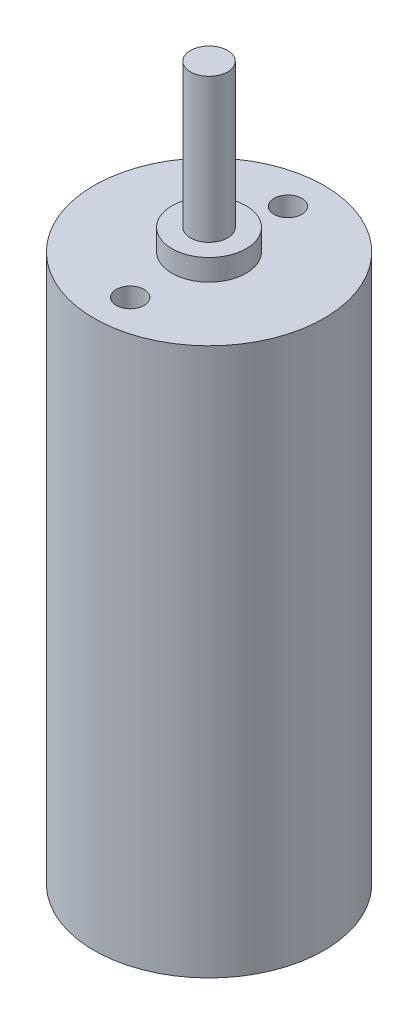
SolidWorks part; units mm, degrees
ref_plane "Front Plane" through (0, 0, 0) normal (0, 0, 1) x (1, 0, 0)
ref_plane "Top Plane" through (0, 0, 0) normal (0, 1, 0) x (1, 0, 0)
ref_plane "Right Plane" through (0, 0, 0) normal (1, 0, 0) x (0, 0, -1)
sketch "Sketch1" plane through (0, 0, 0) normal (0, 1, 0) x (1, 0, 0)
  circle A0 centre (0, 0) radius 12.4
  dimension "D1" = 24.8
extrude "Boss-Extrude1" add sketch "Sketch1" along normal blind 59 contours A0
sketch "Sketch2" plane through (0, 59, 0) normal (0, 1, 0) x (1, 0, 0)
  line L0 (0, 8.5) -> (0, -8.5) construction
  circle A0 centre (0, 8.5) radius 1.5
  circle A1 centre (0, -8.5) radius 1.5
  circle A2 centre (0, 0) radius 3.5
  point P4 (0, 0)
  dimension "D2" = 3
  dimension "D3" = 3
  dimension "D4" = 7
  dimension "D1" = 17
extrude "Cut-Extrude1" cut sketch "Sketch2" against normal blind 3.4798 contours A0 | A1
sketch "Sketch4" plane through (0, 59, 0) normal (0, 1, 0) x (1, 0, 0)
  circle A0 centre (0, 0) radius 4
  dimension "D1" = 8
extrude "Boss-Extrude3" add sketch "Sketch4" along normal blind 2.3
sketch "Sketch5" plane through (0, 61.3, 0) normal (0, 1, 0) x (1, 0, 0)
  circle A0 centre (0, 0) radius 2
  dimension "D1" = 4
extrude "Boss-Extrude4" add sketch "Sketch5" along normal blind 15.5
